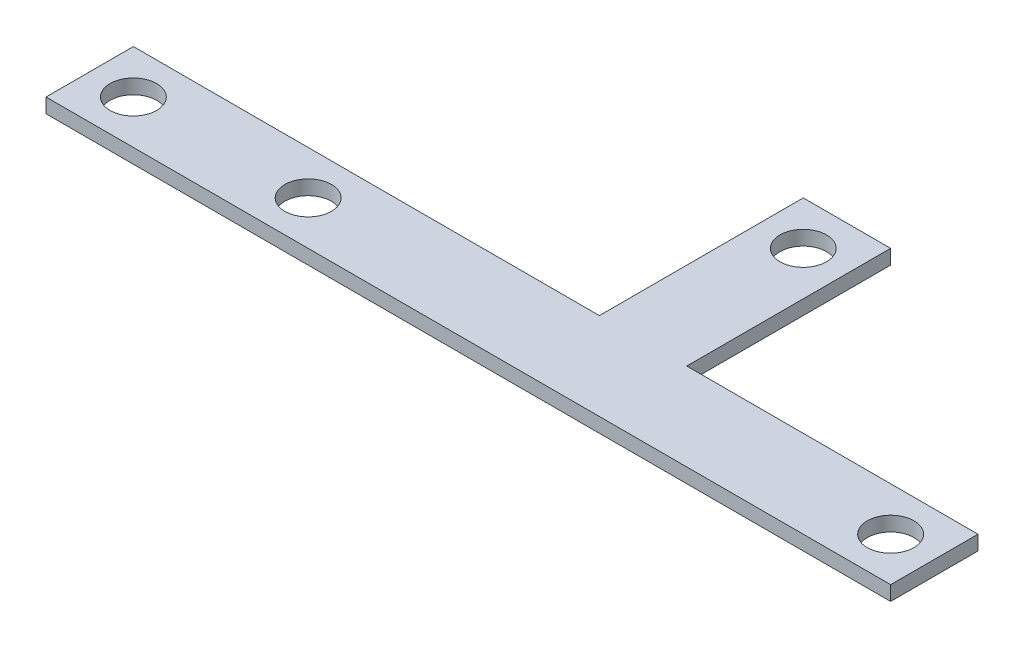
SolidWorks part; units mm, degrees
ref_plane "Ön Düzlem" through (0, 0, 0) normal (0, 0, 1) x (1, 0, 0)
ref_plane "Üst Düzlem" through (0, 0, 0) normal (0, 1, 0) x (1, 0, 0)
ref_plane "Sağ Düzlem" through (0, 0, 0) normal (1, 0, 0) x (0, 0, -1)
sketch "Sketch2" plane through (0, 0, 0) normal (0, 1, 0) x (1, 0, 0)
  line L1 (0, 0) -> (290, 0)
  line L2 (0, 0) -> (0, -30)
  line L3 (0, -30) -> (290, -30)
  line L4 (290, 0) -> (290, -30)
  line L5 (0, 0) -> (290, -30) construction
  line L6 (0, -30) -> (290, 0) construction
  line L7 (160, 70) -> (190, 70)
  line L8 (160, 70) -> (160, -20)
  line L9 (160, -20) -> (190, -20)
  line L10 (190, 70) -> (190, -20)
  line L11 (160, 70) -> (190, -20) construction
  line L12 (160, -20) -> (190, 70) construction
  circle A0 centre (15, -15) radius 8
  circle A1 centre (275, -15) radius 8
  circle A2 centre (175, 55) radius 8
  circle A3 centre (75, -15) radius 8
  point P4 (145, -15)
  point P11 (290, -15)
  point P18 (175, 25)
  dimension "D3" = 16
  dimension "D5" = 16
  dimension "D7" = 16
  dimension "D8" = 160
  dimension "D9" = 100
  dimension "D15" = 16
  dimension "D16" = 60
  dimension "D1" = 30
  dimension "D2" = 290
  dimension "D4" = 260
  dimension "D6" = 15
  dimension "D10" = 70
  dimension "D11" = 90
  dimension "D12" = 30
  dimension "D13" = 15
  dimension "D14" = 15
extrude "Boss-Extrude5" add sketch "Sketch2" along normal blind 5 contours L4 L1 L2 L3 A1 A0 | A2 | L8 L7 L10 L9
